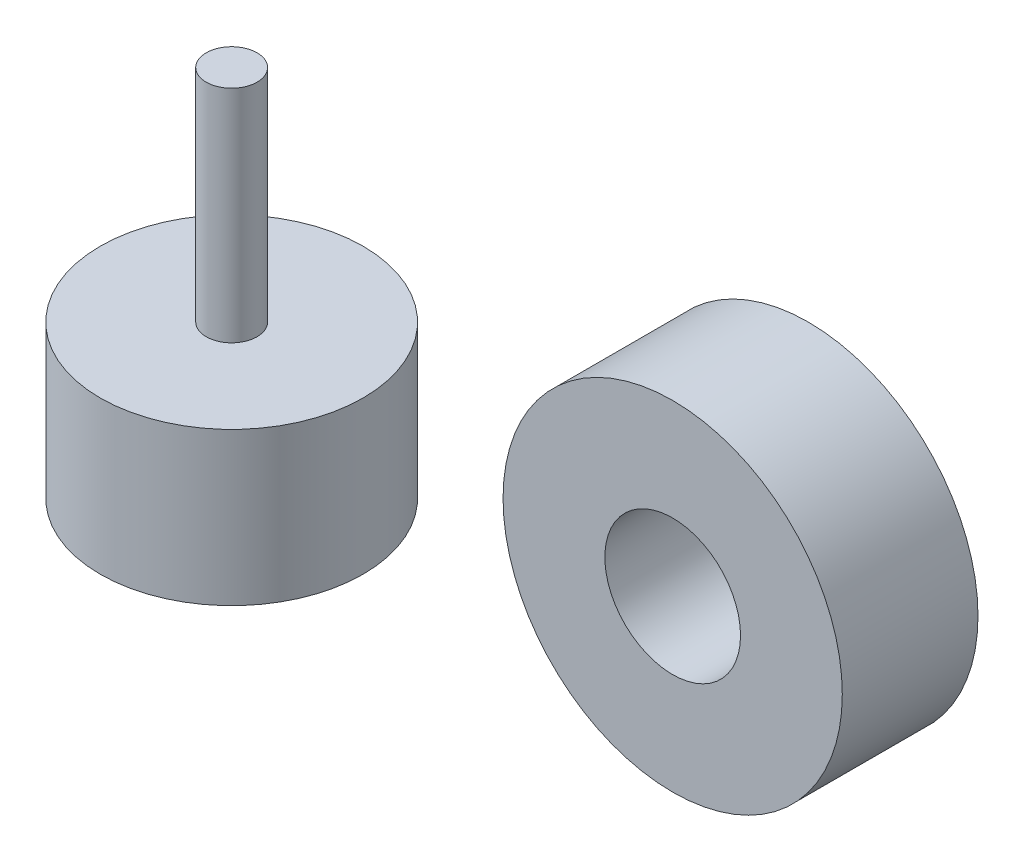
SolidWorks part; units mm, degrees
ref_plane "Front Plane" through (0, 0, 0) normal (0, 0, 1) x (1, 0, 0)
ref_plane "Top Plane" through (0, 0, 0) normal (0, 1, 0) x (1, 0, 0)
ref_plane "Right Plane" through (0, 0, 0) normal (1, 0, 0) x (0, 0, -1)
sketch "rod" plane through (0, 0, 0) normal (0, 0, 1) x (1, 0, 0)
  line L0 (0, 0) -> (30, 0) construction
  circle A0 centre (30, 0) radius 4
  dimension "D2" = 8
  dimension "D1" = 30
sketch "bearing" plane through (0, 0, 0) normal (0, 0, 1) x (1, 0, 0)
  line L0 (0, 0) -> (0, -7.5) construction
  line L2 (-7.75, -12) -> (7.75, -12)
  line L3 (-7.75, -12) -> (-7.75, -3)
  line L4 (-7.75, -3) -> (7.75, -3)
  line L5 (7.75, -12) -> (7.75, -3)
  line L6 (-7.75, -12) -> (7.75, -3) construction
  line L7 (-7.75, -3) -> (7.75, -12) construction
  dimension "D1" = 7.5
  dimension "D2" = 9
  dimension "D3" = 15.5
sketch "Sketch3" plane through (0, 0, 0) normal (0, 0, 1) x (1, 0, 0)
  circle A0 centre (30, 0) radius 4 construction
  circle A1 centre (30, 0) radius 4
  circle A2 centre (30, 0) radius 10
  dimension "D1" = 6
extrude "rod holder" add sketch "Sketch3" along normal mid plane 8
sketch "Sketch4" plane through (0, 0, 0) normal (0, 0, 1) x (1, 0, 0)
  line L1 (7.75, -12) -> (7.75, -3) construction
  line L2 (-7.75, -12) -> (7.75, -12) construction
  line L4 (0, -3) -> (7.75, -3)
  line L5 (7.75, -12) -> (7.75, -3)
  line L6 (0, -12) -> (7.75, -12)
  line L8 (0, -7.5) -> (0, 0) construction
  line L9 (0, -3) -> (0, -12)
revolve "Revolve5" add sketch "Sketch4" angle 360 about L8
sketch "Sketch5" plane through (0, -3, 0) normal (0, 1, 0) x (1, 0, 0)
  line L0 (-7.75, 0) -> (7.75, 0) construction
  circle A0 centre (0, 0) radius 1.5
  dimension "D1" = 3
extrude "Boss-Extrude2" add sketch "Sketch5" along normal blind 13
sketch "pen centerpoint" plane through (0, 0, 0) normal (0, 0, 1) x (1, 0, 0)
  line L0 (0, 0) -> (0, -13) construction
  dimension "D1" = 13
sketch "servo" plane through (0, 0, 0) normal (0, 0, 1) x (1, 0, 0)
  line L0 (6.3512, 8.7928) -> (18.8512, 8.7928) construction
  line L1 (6.3512, 8.7928) -> (6.3512, 31.3928) construction
  line L2 (6.3512, 31.3928) -> (18.8512, 31.3928) construction
  line L3 (18.8512, 8.7928) -> (18.8512, 31.3928) construction
  circle A0 centre (12.6012, 15.0428) radius 6.25 construction
  dimension "D1" = 22.6
  dimension "D2" = 12.5
sketch "gearing" plane through (0, 0, 0) normal (0, 0, 1) x (1, 0, 0)
  line L0 (0, -13) -> (12.6012, 15.0428) construction
  circle A0 centre (0, -13) radius 20.4959
  circle A1 centre (12.6012, 15.0428) radius 10.248
  dimension "D2" = 40.9919
  dimension "D1" = 30.7439
equation "\"D2@gearing\"=\"D1@gearing\"*2*2/3"
